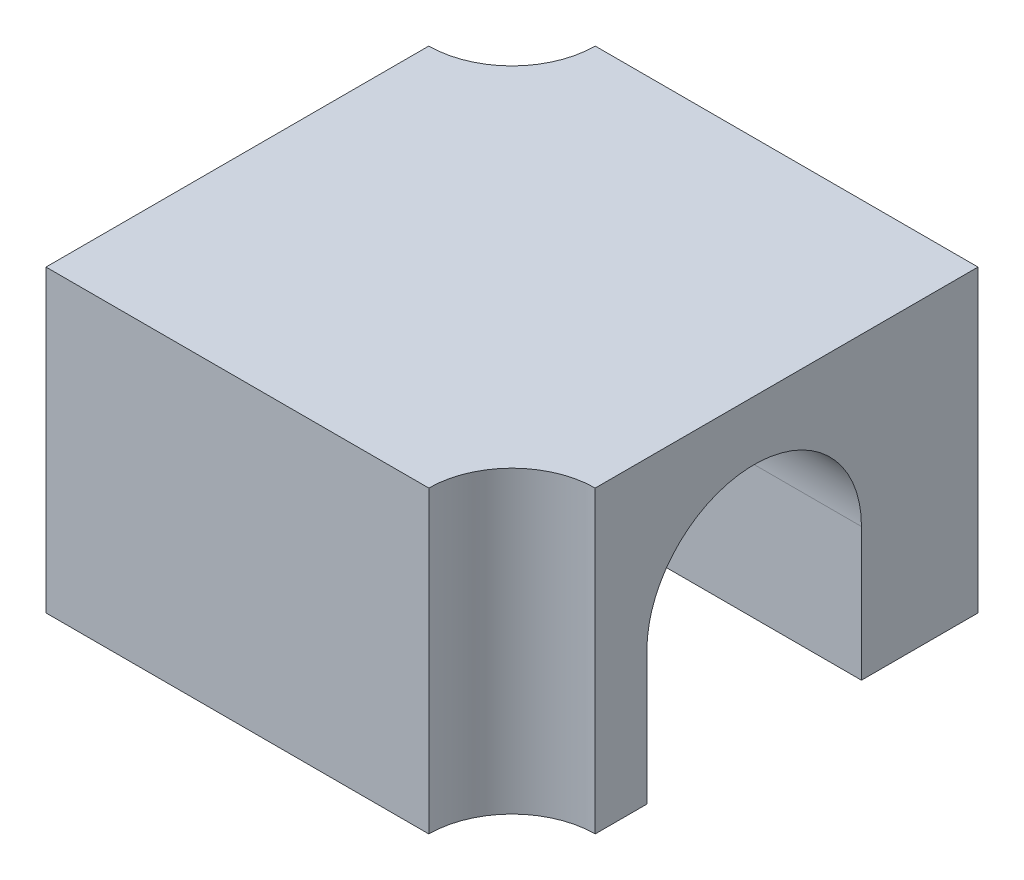
SolidWorks part; units mm, degrees
material "山毛榉"
ref_plane "前视基准面" through (0, 0, 0) normal (0, 0, 1) x (1, 0, 0)
ref_plane "上视基准面" through (0, 0, 0) normal (0, 1, 0) x (1, 0, 0)
ref_plane "右视基准面" through (0, 0, 0) normal (1, 0, 0) x (0, 0, -1)
sketch "草图1" plane through (0, 0, 0) normal (0, 1, 0) x (1, 0, 0)
  line L1 (64.1196, -34.8142) -> (8.1196, -34.8142)
  line L2 (64.1196, -34.8142) -> (64.1196, 21.1858)
  line L3 (64.1196, 21.1858) -> (8.1196, 21.1858)
  line L4 (8.1196, -34.8142) -> (8.1196, 21.1858)
extrude "凸台-拉伸1" add sketch "草图1" along normal blind 36
sketch "草图3" plane through (64.1196, 0, 0) normal (1, 0, 0) x (0, 0, -1)
  line L0 (-18.6065, 16) -> (-18.6065, 0)
  line L1 (-34.8142, 0) -> (21.1858, 0) construction
  line L2 (7.1811, 16) -> (7.1811, 0)
  circle A0 centre (-5.7127, 16) radius 12.8938
  line M2 (-34.8142, 0) -> (21.1858, 0)
extrude "切除-拉伸5" cut sketch "草图3" against normal blind 56 contours A0 | A0 L0 L2 M2
sketch "草图5" plane through (0, 36, 0) normal (0, 1, 0) x (1, 0, 0)
  circle A0 centre (64.1196, -34.8142) radius 10
  circle A1 centre (8.1196, 21.1858) radius 10
  line M1 (64.1196, -34.8142) -> (64.1196, 21.1858)
  line M2 (64.1196, 21.1858) -> (8.1196, 21.1858)
  line M3 (8.1196, 21.1858) -> (8.1196, -34.8142)
  line M4 (8.1196, -34.8142) -> (64.1196, -34.8142)
extrude "切除-拉伸6" cut sketch "草图5" against normal blind 56 contours A0 M1 M4 | A1 M3 M2
